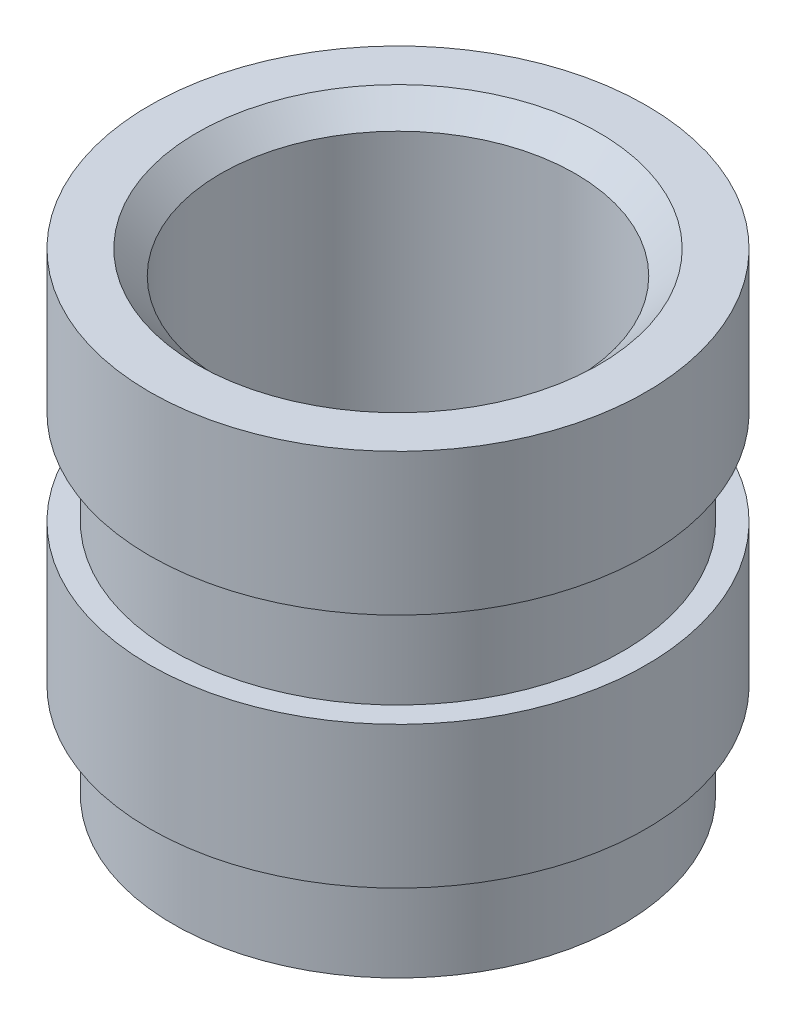
SolidWorks part; units mm, degrees
ref_plane "Front" through (0, 0, 0) normal (0, 0, 1) x (1, 0, 0)
ref_plane "Top" through (0, 0, 0) normal (0, 1, 0) x (1, 0, 0)
ref_plane "Right" through (0, 0, 0) normal (1, 0, 0) x (0, 0, -1)
sketch "草图1" plane through (0, 0, 0) normal (0, 0, 1) x (1, 0, 0)
  line L0 (0, 0) -> (0, 4) construction
  line L1 (1.5, 4) -> (2.1, 4)
  line L2 (2.1, 4) -> (2.1, 2.8)
  line L3 (2.1, 2.8) -> (1.9, 2.8)
  line L4 (1.9, 2.8) -> (1.9, 2)
  line L5 (1.9, 2) -> (2.1, 2)
  line L6 (2.1, 2) -> (2.1, 0.8)
  line L7 (2.1, 0.8) -> (1.9, 0.8)
  line L8 (1.9, 0.8) -> (1.9, 0)
  line L9 (1.9, 0) -> (1.5, 0)
  line L10 (1.5, 0) -> (1.5, 4)
  dimension "D1" = 4
  dimension "D2" = 2.1
  dimension "D3" = 3
  dimension "D4" = 3.8
  dimension "D5" = 0.8
  dimension "D6" = 1.2
revolve "旋转1" add sketch "草图1" angle 360 about L0
chamfer "倒角1" distance 0.2 angle 45 2 edges at (0, 0, -1.5) (0, 4, -1.5)
